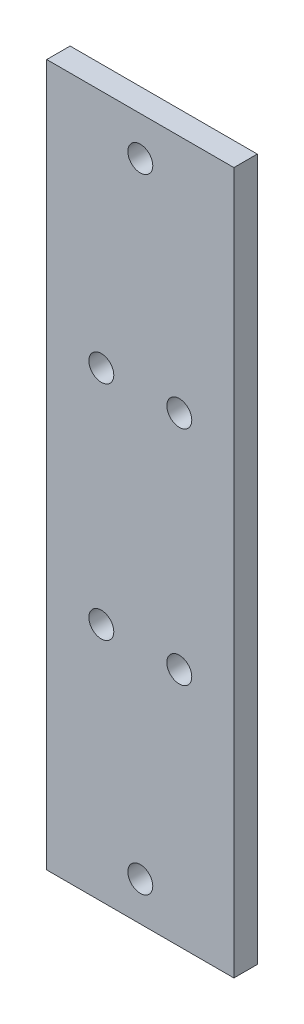
SolidWorks part; units mm, degrees
ref_plane "Front Plane" through (0, 0, 0) normal (0, 0, 1) x (1, 0, 0)
ref_plane "Top Plane" through (0, 0, 0) normal (0, 1, 0) x (1, 0, 0)
ref_plane "Right Plane" through (0, 0, 0) normal (1, 0, 0) x (0, 0, -1)
sketch "Sketch1" plane through (0, 0, 0) normal (0, 0, 1) x (1, 0, 0)
  line L0 (17, 59.25) -> (24, 59.25) construction
  line L1 (0, 0) -> (24, 0)
  line L2 (0, 0) -> (0, 90)
  line L3 (0, 90) -> (24, 90)
  line L4 (24, 0) -> (24, 90)
  line L5 (7, 59.25) -> (0, 59.25) construction
  line L6 (7, 59.25) -> (7, 90) construction
  line L7 (7, 30.75) -> (7, 0) construction
  line L8 (12, 85) -> (12, 90) construction
  line L9 (12, 0) -> (12, 5) construction
  circle A0 centre (7, 59.25) radius 1.6
  circle A1 centre (17, 59.25) radius 1.6
  circle A2 centre (7, 30.75) radius 1.6
  circle A3 centre (17, 30.75) radius 1.6
  circle A4 centre (12, 85) radius 1.6
  circle A5 centre (12, 5) radius 1.6
  dimension "D5" = 3.2
  dimension "D1" = 10
  dimension "D2" = 28.5
  dimension "D3" = 24
  dimension "D4" = 90
  dimension "D6" = 5
extrude "Boss-Extrude1" add sketch "Sketch1" along normal blind 3
